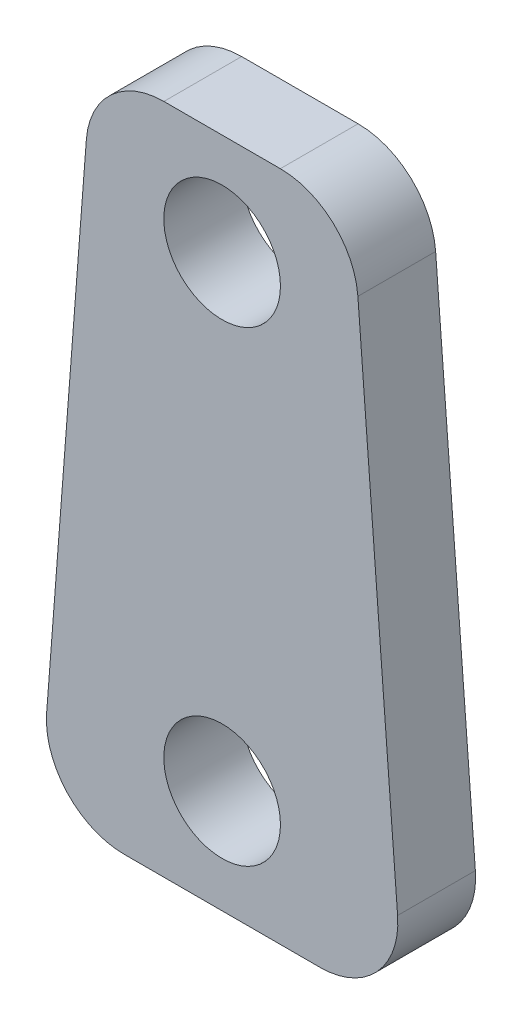
SolidWorks part; units mm, degrees
ref_plane "Front Plane" through (0, 0, 0) normal (0, 0, 1) x (1, 0, 0)
ref_plane "Top Plane" through (0, 0, 0) normal (0, 1, 0) x (1, 0, 0)
ref_plane "Right Plane" through (0, 0, 0) normal (1, 0, 0) x (0, 0, -1)
sketch "Sketch1" plane through (0, 0, 0) normal (0, 0, 1) x (1, 0, 0)
  line L4 (5.5432, 134.3132) -> (7.1649, 113.2312)
  line L8 (-3.9993, 109.8127) -> (3.9993, 109.8127)
  line L9 (-2.3776, 137.2447) -> (2.3776, 137.2447)
  line L11 (0, 109.8127) -> (0, 137.2447)
  line L12 (-7.1649, 113.2312) -> (-5.5432, 134.3132)
  circle A0 centre (0, 133.096) radius 2.3812
  circle A1 centre (0, 114.046) radius 2.3812
  arc A2 (7.1649, 113.2312) -> (3.9993, 109.8127) centre (3.9993, 112.9877) cw
  arc A3 (-7.1649, 113.2312) -> (-3.9993, 109.8127) centre (-3.9993, 112.9877) ccw
  arc A4 (-5.5432, 134.3132) -> (-2.3776, 137.2447) centre (-2.3776, 134.0697) cw
  arc A5 (5.5432, 134.3132) -> (2.3776, 137.2447) centre (2.3776, 134.0697) ccw
  dimension "D1" = 19.05
  dimension "D2" = 4.2333
  dimension "D3" = 4.7625
  dimension "D4" = 4.7625
  dimension "D5" = 3.175
extrude "Boss-Extrude1" add sketch "Sketch1" along normal blind 3.175 contours A4 L12 A3 L8 L11 A1 A0 L9 | L4 A5 L9 L11 A0 A1 L8 A2
